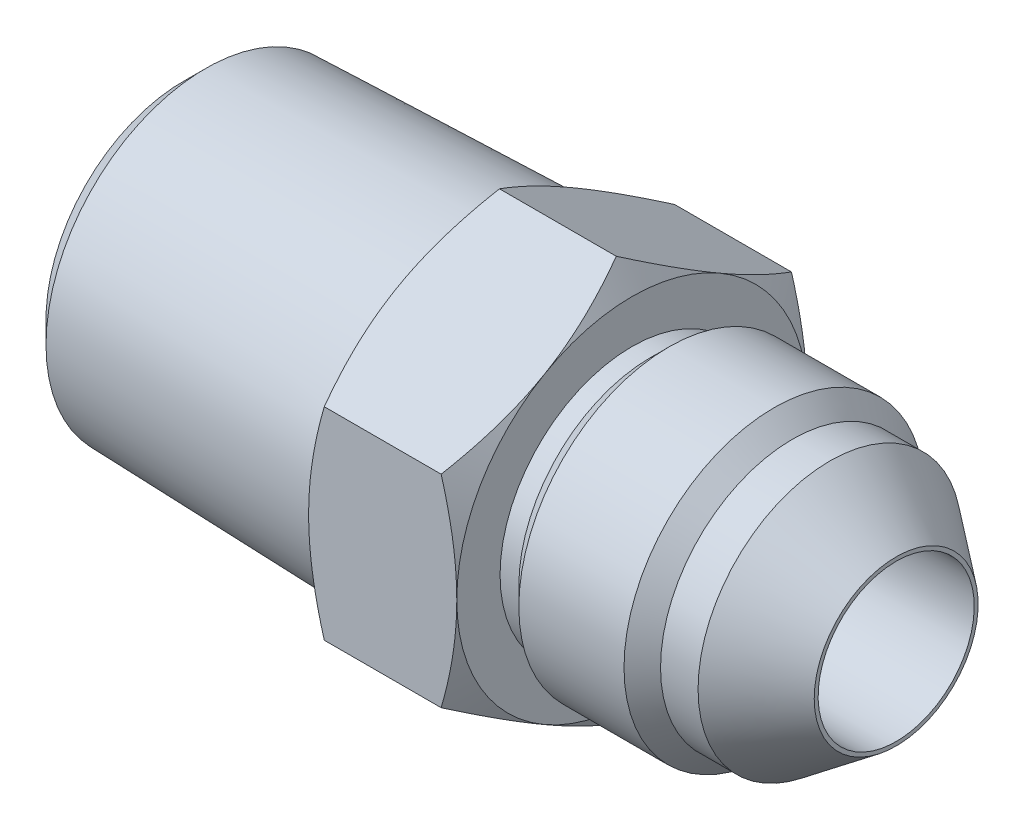
SolidWorks part; units mm, degrees
ref_plane "Front" through (0, 0, 0) normal (0, 0, 1) x (1, 0, 0)
ref_plane "Top" through (0, 0, 0) normal (0, 1, 0) x (1, 0, 0)
ref_plane "Right" through (0, 0, 0) normal (1, 0, 0) x (0, 0, -1)
sketch "Sketch6" plane through (0, 0, 0) normal (0, 0, 1) x (1, 0, 0)
  line L0 (-3.556, 10.668) -> (-3.556, -10.668) construction
  line L1 (22.606, 9.525) -> (22.606, -9.525) construction
  line L2 (-22.606, 0) -> (22.606, 0)
  line L4 (-22.606, 0) -> (-22.606, 9.525)
  line L5 (-22.606, 9.525) -> (22.606, 9.525)
  line L6 (22.606, 0) -> (22.606, 9.525)
  line L7 (-22.606, 4.953) -> (-22.606, -4.953) construction
  line L8 (-3.556, 11.8745) -> (-3.556, -11.8745) construction
  line L9 (5.842, 11.8745) -> (5.842, -11.8745) construction
  point P4 (5.842, 0)
  point P6 (-3.556, 0)
  dimension "Straight Dia" = 19.05
  dimension "Length" = 45.212
  dimension "L1" = 16.764
  dimension "Pipe OD" = 21.336
  dimension "L2" = 19.05
  dimension "D1" = 9.906
  dimension "D2" = 23.749
revolve "Revolve3" add sketch "Sketch6" angle 360 about L2
sketch "Sketch14" plane through (22.606, 0, 0) normal (-1, 0, 0) x (0, 0, 1)
  circle A1 centre (0, 0) radius 9.525
  circle A2 centre (0, 0) radius 9.525
  dimension "D1" = 0
curve "Helix/Spiral1" pitch 1.5875 height 18.3515 turns 11.56 parameters "Pitch"=1.5875
sketch "Sketch15" plane through (0, 0, 0) normal (0, 0, 1) x (1, 0, 0)
  line L0 (22.606, 9.525) -> (23.9951, 9.525)
  line L1 (23.9951, 9.525) -> (23.3997, 8.4939)
  line L2 (23.3997, 8.4939) -> (23.2013, 8.4939)
  line L3 (23.2013, 8.4939) -> (22.606, 9.525)
  line L4 (23.3005, 8.4939) -> (23.3005, 9.525) construction
  line L5 (22.9037, 9.0094) -> (23.6974, 9.0094) construction
  dimension "D1" = 60
  dimension "D2" = 0.1984
  dimension "D3" = 0.7937
ref_plane "Plane1" through (-3.556, 0, 0) normal (1, 0, 0) x (0, 0, -1)
sketch "Sketch12" plane through (-3.556, 0, 0) normal (1, 0, 0) x (0, 0, -1)
  line L1 (0, 12.8316) -> (-11.1125, 6.4158)
  line L2 (-11.1125, 6.4158) -> (-11.1125, -6.4158)
  line L3 (-11.1125, -6.4158) -> (0, -12.8316)
  line L4 (0, -12.8316) -> (11.1125, -6.4158)
  line L5 (11.1125, -6.4158) -> (11.1125, 6.4158)
  line L6 (11.1125, 6.4158) -> (0, 12.8316)
  circle A0 centre (0, 0) radius 11.1125 construction
  dimension "Hex" = 22.225
extrude "Extrude1" add sketch "Sketch12" along normal up to vertex (9.398 mm away) up to point (5.842, 0, 0)
sketch "Sketch7" plane through (0, 0, 0) normal (0, 0, 1) x (1, 0, 0)
  line L0 (-22.606, 0) -> (-22.606, 4.953)
  line L2 (-22.606, 4.953) -> (22.606, 4.953)
  line L4 (22.606, 0) -> (22.606, 9.525) construction
  line L11 (22.606, 4.953) -> (22.606, 0)
  line L12 (22.606, 0) -> (-22.606, 0)
  line L13 (-22.606, 4.953) -> (-22.606, -4.953) construction
  dimension "ID" = 9.906
sketch "Sketch10" plane through (0, 0, 0) normal (0, 0, 1) x (1, 0, 0)
  line L0 (-22.606, 9.525) -> (22.606, 9.525) construction
  line L1 (22.606, 9.525) -> (23.9951, 9.525) construction
  line L2 (-3.556, -10.668) -> (-22.606, -10.0859) construction
  line L3 (5.842, 12.8316) -> (5.842, 6.4158) construction
  line L5 (0, 0) -> (-22.606, 0) construction
  line L6 (8.1907, 9.525) -> (5.842, 9.525)
  line L9 (5.842, 8.3669) -> (5.842, 9.525)
  line L21 (22.606, 9.525) -> (14.8649, 9.525)
  line L22 (14.8649, 9.525) -> (16.023, 8.3669)
  line L23 (16.023, 8.3669) -> (18.4043, 8.3669)
  line L24 (18.4043, 8.3669) -> (22.606, 5.2007)
  line L25 (22.606, 5.2007) -> (22.606, 9.525)
  line L26 (7.0326, 8.3669) -> (5.842, 8.3669)
  line L27 (8.1907, 9.525) -> (7.0326, 8.3669)
  point P5 (12.848, -9.525)
  point P9 (-14.4417, -10.3354)
  dimension "D1" = 10.4013
  dimension "D2" = 37
  dimension "D3" = 2.3813
  dimension "D5" = 45
  dimension "D4" = 1.1906
  dimension "D6" = 3.175
  dimension "D7" = 0.127
  dimension "D9" = 8.1643
  dimension "D8" = 1.75
revolve "Cut-Revolve6" cut sketch "Sketch10" angle 360 about L2
revolve "Cut-Revolve5" cut sketch "Sketch7" angle 360 about L12
sketch "Sketch13" plane through (0, 0, 0) normal (0, 0, 1) x (1, 0, 0)
  line L0 (-3.556, 12.8316) -> (-3.556, 11.1125)
  line L1 (-3.556, 6.4158) -> (-3.556, 12.8316) construction
  line L2 (-3.556, 11.1125) -> (-2.5635, 12.8316)
  line L3 (-2.5635, 12.8316) -> (-3.556, 12.8316)
  line L4 (4.8495, 12.8316) -> (5.842, 11.1125)
  line L5 (5.842, 12.8316) -> (5.842, 6.4158) construction
  line L6 (5.842, 11.1125) -> (5.842, 12.8316)
  line L7 (5.842, 12.8316) -> (4.8495, 12.8316)
  dimension "D2" = 30
revolve "Cut-Revolve7" cut sketch "Sketch13" angle 360 about L2
sketch "Sketch17" plane through (-22.606, 0, 0) normal (-1, 0, 0) x (0, 0, 1)
  circle A0 centre (0, 0) radius 9.525 construction
  circle A1 centre (0, 0) radius 9.525
extrude "Cut-Extrude1" cut sketch "Sketch17" against normal up to vertex (19.05 mm away) up to point (-3.556, 0, 0)
ref_plane "Plane2" through (-3.556, 0, 0) normal (1, 0, 0) x (0, 0, -1)
sketch "Sketch19" plane through (-3.556, 0, 0) normal (1, 0, 0) x (0, 0, -1)
  circle A0 centre (0, 0) radius 10.668
extrude "Boss-Extrude1" add sketch "Sketch19" against normal up to vertex (19.05 mm away) draft 1.75 separate body up to point (-22.606, 0, 0)
sketch "Sketch20" plane through (-22.606, 0, 0) normal (1, 0, 0) x (0, 0, -1)
  circle A1 centre (0, 0) radius 10.086
  circle A2 centre (0, 0) radius 10.086 construction
sketch "Sketch21" plane through (0, 0, 0) normal (0, 0, 1) x (1, 0, 0)
  line L0 (-24.2122, 9.9659) -> (-22.6753, 9.9659) construction
  line L1 (-24.3509, 10.2061) -> (-23.4438, 8.6349) construction
  line L2 (-23.5639, 8.8429) -> (-23.3237, 8.8429)
  line L3 (-23.4438, 8.6349) -> (-22.5367, 10.2061) construction
  line L4 (-23.4438, 8.6349) -> (-23.3237, 8.8429) construction
  line L5 (-23.4438, 9.9659) -> (-23.4438, 10.2061) construction
  line L6 (-24.3509, 10.2061) -> (-22.5367, 10.2061) construction
  line L7 (-23.4438, 10.086) -> (-22.606, 10.086) construction
  line L8 (-22.5367, 10.2061) -> (-24.2816, 10.086)
  line L9 (-24.2816, 10.086) -> (-23.5639, 8.8429)
  line L10 (-23.3237, 8.8429) -> (-22.5367, 10.2061)
  line L11 (-23.4438, 8.6349) -> (-23.4438, 8.8429) construction
  dimension "D2" = 0.2402
  dimension "D1" = 1.8143
curve "Helix/Spiral2" parameters "Pitch"=1.8143
chamfer "Chamfer1" distance 1.3607 angle 45 1 edges at (-22.606, 0, -10.086)
sketch "Sketch22" plane through (-3.556, 0, 0) normal (1, 0, 0) x (0, 0, -1)
  circle A1 centre (0, 0) radius 10.668
  circle A2 centre (0, 0) radius 10.668
  dimension "D1" = 0
extrude "Boss-Extrude3" add sketch "Sketch22" against normal up to vertex (19.05 mm away) draft 15 up to point (-22.606, 9.525, 0)
combine bodies "Combine1" operation type add bodies to combine 173 169
sketch "Sketch23" plane through (-22.606, 0, 0) normal (-1, 0, 0) x (0, 0, 1)
  circle A2 centre (0, 0) radius 4.953
extrude "Cut-Extrude2" cut sketch "Sketch23" against normal up to vertex (19.05 mm away) up to point (-3.556, 0, 0)
equation "\"D3@Helix/Spiral1\" = \"L1@Sketch6\"+\"Pitch@Helix/Spiral1\""
equation "\"D2@Sketch15\" = \"Pitch@Helix/Spiral1\"*.125"
equation "\"D3@Sketch15\" = \"Pitch@Helix/Spiral1\"*.5"
equation "\"D3@Sketch10\" = \"Pitch@Helix/Spiral1\"*1.5"
equation "\"D1@Sketch10\" = \"ID@Sketch7\"*1.05"
equation "\"D1@Sketch21\" = \"Pitch@Helix/Spiral2\""
equation "\"D3@Helix/Spiral2\" = \"L2@Sketch6\"+\"Pitch@Helix/Spiral2\""
equation "\"D1@Chamfer1\" = \"Pitch@Helix/Spiral2\"*.75"
equation "\"D4@Sketch10\" = \"Pitch@Helix/Spiral1\"*.75"
equation "\"D6@Sketch10\" = \"Pitch@Helix/Spiral1\"*2"
equation "\"D9@Sketch10\" = \"Pitch@Helix/Spiral2\"*4.5"
equation "\"D2@Sketch6\" = \"Hex@Sketch12\"+.06"
